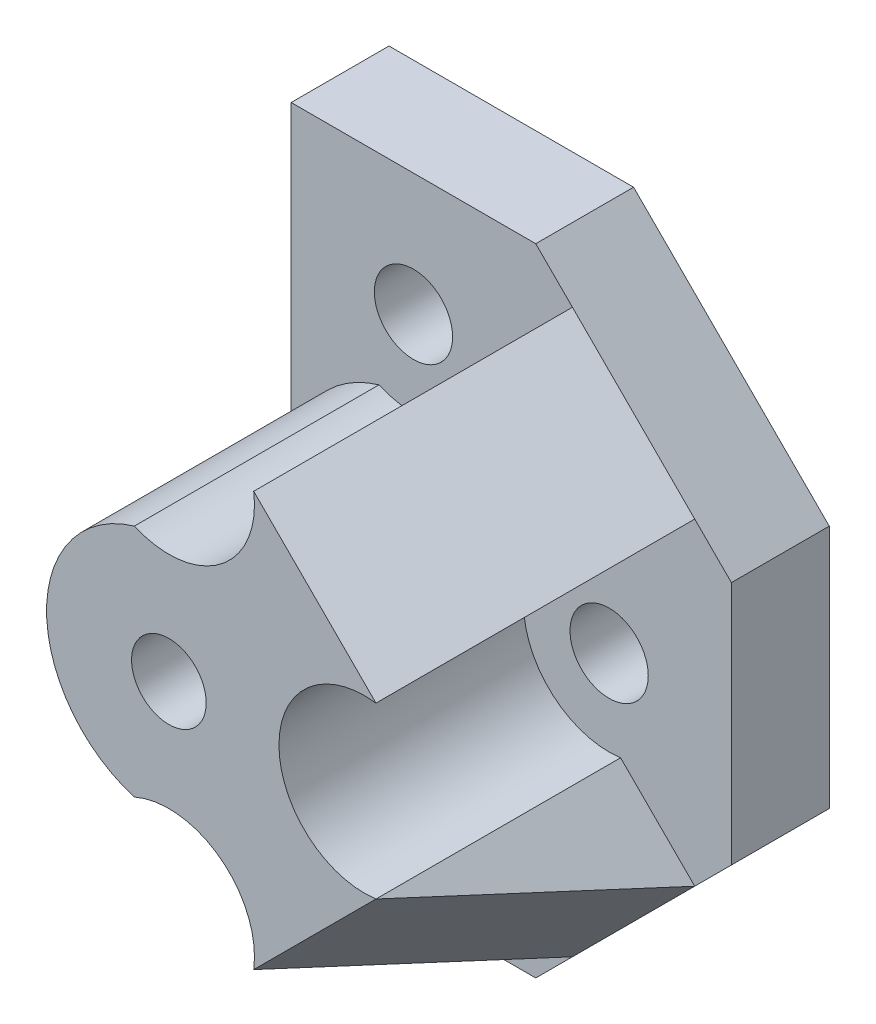
SolidWorks part; units mm, degrees
ref_plane "前视基准面" through (0, 0, 0) normal (0, 0, 1) x (1, 0, 0)
ref_plane "上视基准面" through (0, 0, 0) normal (0, 1, 0) x (1, 0, 0)
ref_plane "右视基准面" through (0, 0, 0) normal (1, 0, 0) x (0, 0, -1)
sketch "草图1" plane through (0, 0, 0) normal (0, 0, 1) x (1, 0, 0)
  line L0 (0, 0) -> (0, 26)
  line L1 (0, 26) -> (10, 26)
  line L2 (18, 18) -> (10, 26)
  line L3 (10, 0) -> (18, 8)
  line L4 (18, 18) -> (18, 8)
  line L7 (10, 0) -> (0, 0)
  circle A0 centre (5, 21) radius 1.6
  circle A1 centre (5, 13) radius 3.2
  circle A2 centre (5, 5) radius 1.6
  circle A3 centre (13, 13) radius 1.6
extrude "凸台-拉伸1" add sketch "草图1" along normal blind 4
sketch "草图2" plane through (0, 0, 4) normal (0, 0, 1) x (1, 0, 0)
  line L1 (13.4685, 16.4685) -> (16.5, 19.5)
  line L2 (18, 18) -> (10, 26) construction
  line L3 (16.5, 19.5) -> (11.5, 24.5)
  line L4 (11.5, 24.5) -> (8.4685, 21.4685)
  line L5 (8.4685, 4.5315) -> (11.5, 1.5)
  line L6 (10, 0) -> (18, 8) construction
  line L7 (11.5, 1.5) -> (16.5, 6.5)
  line L8 (16.5, 6.5) -> (13.4685, 9.5315)
  circle A0 centre (5, 13) radius 1.525
  arc A1 (3.5893, 17.7969) -> (3.5893, 8.2031) centre (5, 13) ccw
  arc A5 (8.4685, 4.5315) -> (3.5893, 8.2031) centre (5, 5) ccw
  arc A6 (13.4685, 16.4685) -> (13.4685, 9.5315) centre (13, 13) ccw
  arc A7 (3.5893, 17.7969) -> (8.4685, 21.4685) centre (5, 21) ccw
  dimension "D1" = 3.05
extrude "凸台-拉伸2" add sketch "草图2" along normal blind 10
sketch "草图3" plane through (-1.5, 1.5, 0) normal (0.7071, -0.7071, 0) x (0, 0, -1)
  line L0 (-4, 25.4558) -> (-14, 25.4558)
  line L1 (-14, 25.4558) -> (-14, 21.1687)
  line L2 (-14, 21.1687) -> (-4, 25.4558)
  line L3 (-14, 21.1687) -> (-4, 21.1687) construction
  line L4 (-14, 21.1687) -> (-14, 25.4558) construction
extrude "切除-拉伸1" cut sketch "草图3" against normal blind 10
sketch "草图4" plane through (11.5, 11.5, 0) normal (0.7071, 0.7071, 0) x (0, 0, -1)
  line L0 (-4, -7.0711) -> (-14, -2.7839)
  line L1 (-14, -2.7839) -> (-14, -7.0711)
  line L2 (-14, -7.0711) -> (-4, -7.0711)
  line L3 (-14, -2.7839) -> (-4, -2.7839) construction
extrude "切除-拉伸2" cut sketch "草图4" against normal blind 10
